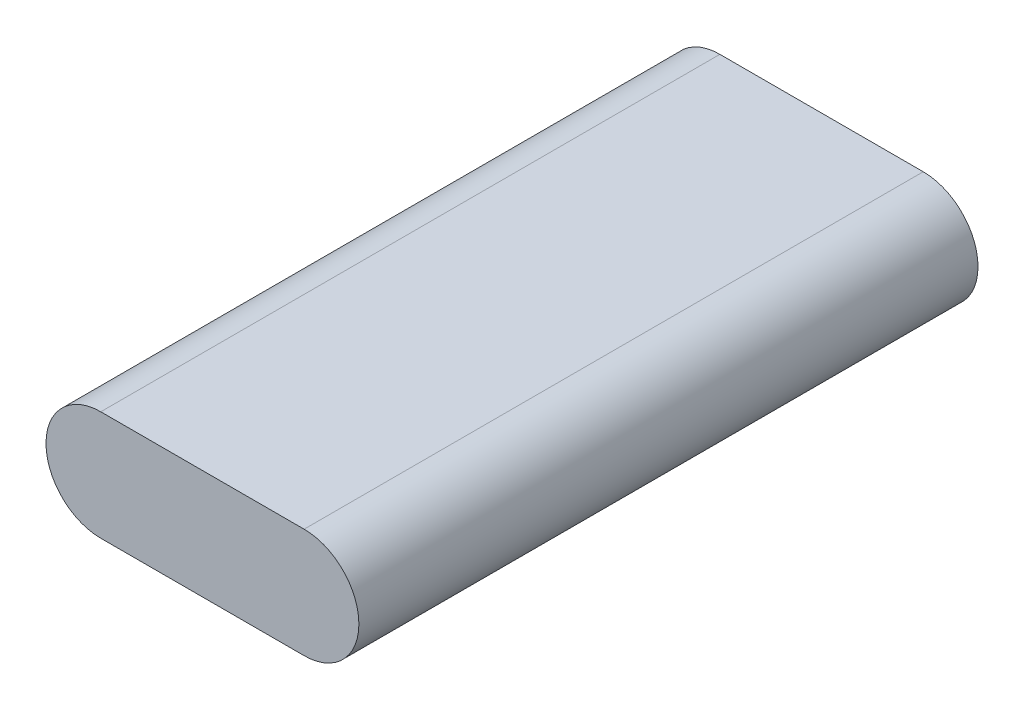
SolidWorks part; units mm, degrees
ref_plane "Plan de face" through (0, 0, 0) normal (0, 0, 1) x (1, 0, 0)
ref_plane "Plan de dessus" through (0, 0, 0) normal (0, 1, 0) x (1, 0, 0)
ref_plane "Plan de droite" through (0, 0, 0) normal (1, 0, 0) x (0, 0, -1)
sketch "Esquisse2" plane through (0, 0, 0) normal (0, 0, 1) x (1, 0, 0)
  line L0 (0, -10.0435) -> (42.7, -10.0435) construction
  line L1 (0, 1.4565) -> (42.7, 1.4565)
  line L2 (0, -21.5435) -> (42.7, -21.5435)
  arc A0 (0, 1.4565) -> (0, -21.5435) centre (0, -10.0435) ccw
  arc A1 (42.7, -21.5435) -> (42.7, 1.4565) centre (42.7, -10.0435) ccw
  point P2 (21.35, -10.0435)
extrude "Boss.-Extru.1" add sketch "Esquisse2" along normal blind 130
